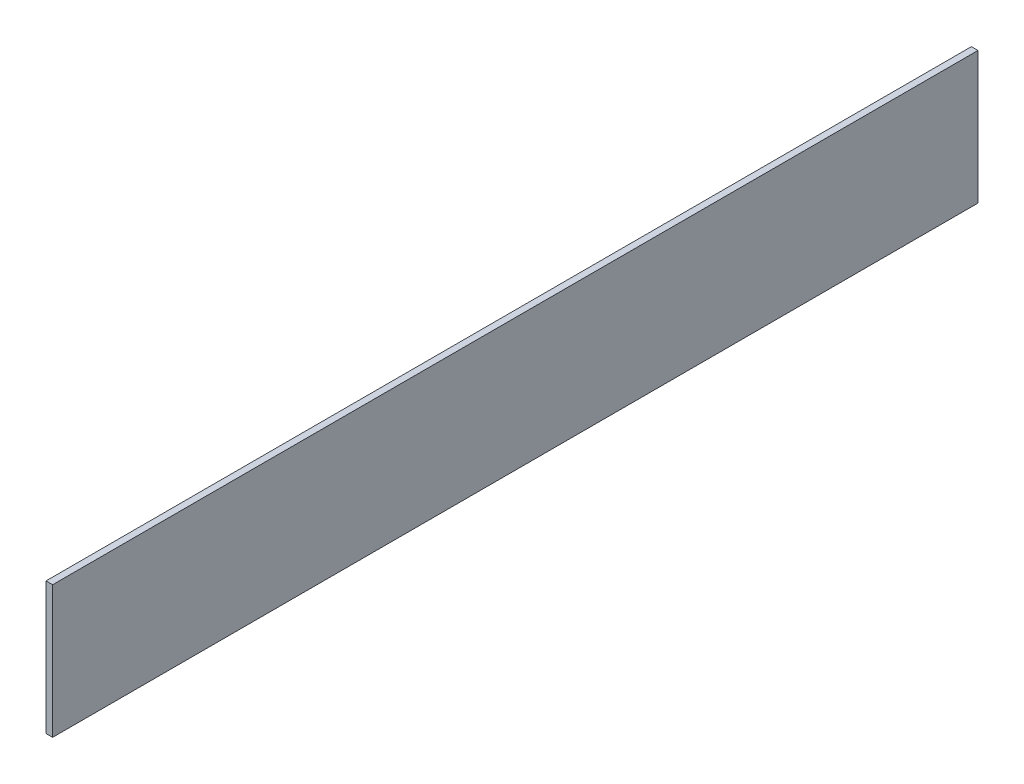
SolidWorks part; units mm, degrees
ref_plane "Front Plane" through (0, 0, 0) normal (0, 0, 1) x (1, 0, 0)
ref_plane "Top Plane" through (0, 0, 0) normal (0, 1, 0) x (1, 0, 0)
ref_plane "Right Plane" through (0, 0, 0) normal (1, 0, 0) x (0, 0, -1)
other "Configuration Table"
sketch "Sketch1" plane through (0, 0, 0) normal (0, 0, 1) x (1, 0, 0)
  line L1 (349, 360) -> (351, 360)
  line L2 (349, 360) -> (349, 400)
  line L3 (349, 400) -> (351, 400)
  line L4 (351, 360) -> (351, 400)
extrude "OVEN_kesme_bicak_2_2x28_t1.2_1" add sketch "Sketch1" against normal blind 280 from offset 160 separate body
